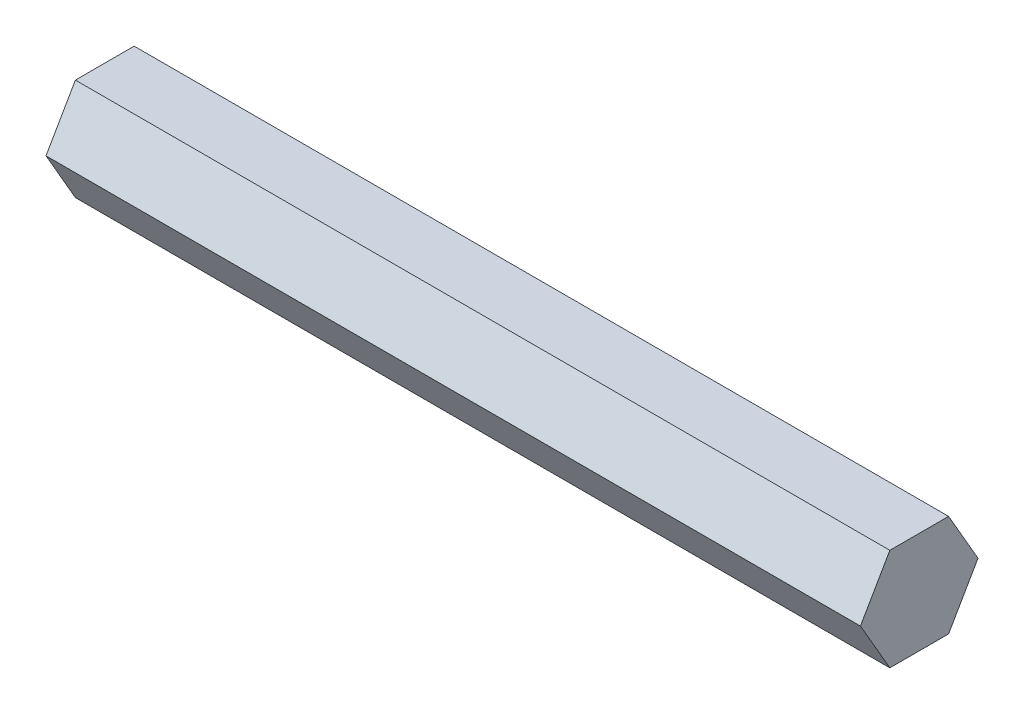
SolidWorks part; units mm, degrees
ref_plane "Front Plane" through (0, 0, 0) normal (0, 0, 1) x (1, 0, 0)
ref_plane "Top Plane" through (0, 0, 0) normal (0, 1, 0) x (1, 0, 0)
ref_plane "Right Plane" through (0, 0, 0) normal (1, 0, 0) x (0, 0, -1)
sketch "Sketch1" plane through (0, 0, 0) normal (1, 0, 0) x (0, 0, -1)
  line L1 (7.3323, 0) -> (3.6662, 6.35)
  line L2 (3.6662, 6.35) -> (-3.6662, 6.35)
  line L3 (-3.6662, 6.35) -> (-7.3323, 0)
  line L4 (-7.3323, 0) -> (-3.6662, -6.35)
  line L5 (-3.6662, -6.35) -> (3.6662, -6.35)
  line L6 (3.6662, -6.35) -> (7.3323, 0)
  circle A2 centre (0, 0) radius 6.35 construction
  dimension "D1" = 12.7
extrude "Boss-Extrude1" add sketch "Sketch1" along normal mid plane 101.6
sketch "Sketch2" plane through (50.8, 0, 0) normal (1, 0, 0) x (0, 0, -1)
  circle A0 centre (0, 0) radius 6.35
  dimension "D1" = 12.7
equation "\"D1@Boss-Extrude1\"=2.3227+0.313+0.005"
